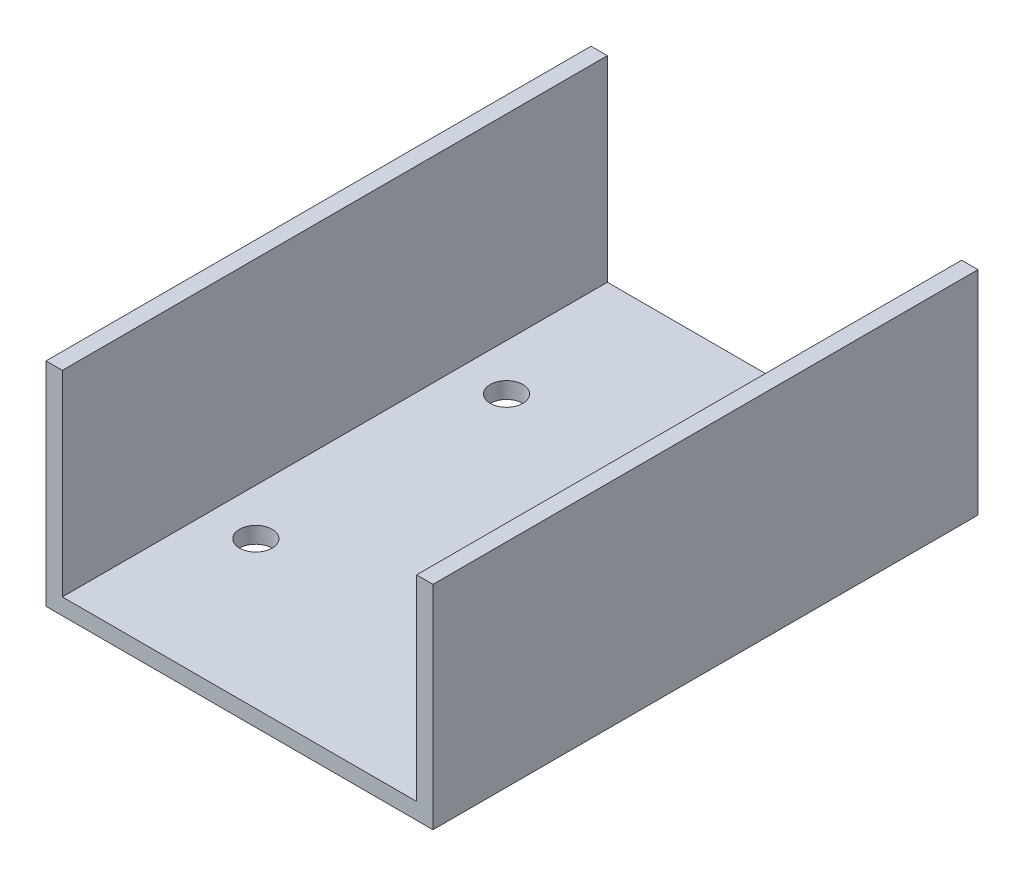
SolidWorks part; units mm, degrees
material "3.0205 (EN-AW 1200)"
ref_plane "Plan de face" through (0, 0, 0) normal (0, 0, 1) x (1, 0, 0)
ref_plane "Plan de dessus" through (0, 0, 0) normal (0, 1, 0) x (1, 0, 0)
ref_plane "Plan de droite" through (0, 0, 0) normal (1, 0, 0) x (0, 0, -1)
sketch "Esquisse1" plane through (0, 0, 0) normal (0, 0, 1) x (1, 0, 0)
  line L0 (-17.75, 19.5) -> (-17.75, 0)
  line L1 (-17.75, 0) -> (17.75, 0)
  line L2 (17.75, 0) -> (17.75, 19.5)
  dimension "D1" = 19.5
  dimension "D2" = 35.5
extrude "Extru.-Mince1" add sketch "Esquisse1" along normal mid plane 50 thin thin type one direction reverse wall 1.5
sketch "Esquisse2" plane through (0, 0, 0) normal (0, -1, 0) x (1, 0, 0)
  line L0 (0, -10.725) -> (0, 10.725) construction
  line L6 (10.725, 0) -> (-10.725, 0) construction
  circle A2 centre (-12, 11.5) radius 1.5
  circle A3 centre (-12, -11.5) radius 1.5
  circle A4 centre (12, -11.5) radius 1.5
  circle A5 centre (12, 11.5) radius 1.5
  dimension "D5" = 23
  dimension "D7" = 3
  dimension "D1" = 24
extrude "Enlèv. mat.-Extru.1" cut sketch "Esquisse2" against normal blind 3
